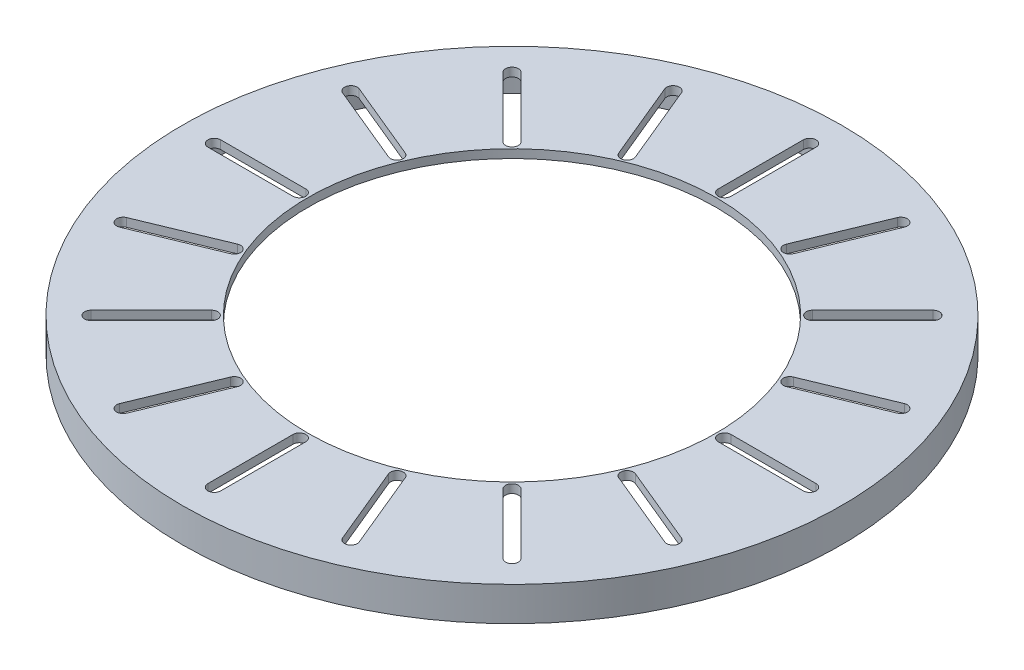
SolidWorks part; units mm, degrees
ref_plane "Front Plane" through (0, 0, 0) normal (0, 0, 1) x (1, 0, 0)
ref_plane "Top Plane" through (0, 0, 0) normal (0, 1, 0) x (1, 0, 0)
ref_plane "Right Plane" through (0, 0, 0) normal (1, 0, 0) x (0, 0, -1)
sketch "Sketch1" plane through (0, 0, 0) normal (0, 1, 0) x (1, 0, 0)
  circle A0 centre (0, 0) radius 37.6
  circle A1 centre (0, 0) radius 38.75
  dimension "D1" = 75.2
  dimension "D2" = 77.5
extrude "Boss-Extrude1" add sketch "Sketch1" along normal blind 3
sketch "Sketch2" plane through (0, 3, 0) normal (0, 1, 0) x (1, 0, 0)
  circle A0 centre (0, 0) radius 38.75
  circle A1 centre (0, 0) radius 24
  circle A2 centre (0, 0) radius 38.75 construction
  dimension "D1" = 48
extrude "Boss-Extrude2" add sketch "Sketch2" along normal blind 1
sketch "Sketch3" plane through (0, 4, 0) normal (0, 1, 0) x (1, 0, 0)
  line L0 (0, 0) -> (0, 31.25) construction
  line L1 (8, 31.25) -> (8, 34.6962) construction
  line L2 (0, 31.25) -> (8, 31.25) construction
  line L3 (8, 34.6962) -> (-8, 27.8038) construction
  line L4 (0, 31.25) -> (-8, 31.25) construction
  line L5 (-8, 31.25) -> (-8, 27.8038) construction
  line L6 (0, 31.25) -> (12.3634, 2.5497) construction
  line L7 (0, 0) -> (-8, 27.8038) construction
  arc A0 (-8, 27.8038) -> (8, 34.6962) centre (12.3634, 2.5497) cw construction
  arc A1 (7.8991, 35.4394) -> (-8.4708, 28.3876) centre (12.3634, 2.5497) ccw
  arc A2 (8.1009, 33.953) -> (-7.5292, 27.2199) centre (12.3634, 2.5497) ccw
  arc A3 (8.1009, 33.953) -> (7.8991, 35.4394) centre (8, 34.6962) ccw
  arc A4 (-8.4708, 28.3876) -> (-7.5292, 27.2199) centre (-8, 27.8038) ccw
  arc A5 (3.249, 28.7488) -> (20.6687, 28.9937) centre (12.398, -2.3757) cw construction
  arc A6 (20.8599, 29.7189) -> (3.0375, 29.4684) centre (12.398, -2.3757) ccw
  arc A7 (20.4775, 28.2684) -> (3.4605, 28.0293) centre (12.398, -2.3757) ccw
  arc A8 (20.4775, 28.2684) -> (20.8599, 29.7189) centre (20.6687, 28.9937) ccw
  arc A9 (3.0375, 29.4684) -> (3.4605, 28.0293) centre (3.249, 28.7488) ccw
  arc A10 (14.0034, 25.3171) -> (30.1908, 18.8771) centre (10.5452, -6.9394) cw construction
  arc A11 (30.645, 19.4739) -> (14.0833, 26.0628) centre (10.5452, -6.9394) ccw
  arc A12 (29.7366, 18.2802) -> (13.9234, 24.5714) centre (10.5452, -6.9394) ccw
  arc A13 (29.7366, 18.2802) -> (30.645, 19.4739) centre (30.1908, 18.8771) ccw
  arc A14 (14.0833, 26.0628) -> (13.9234, 24.5714) centre (14.0034, 25.3171) ccw
  arc A15 (22.6259, 18.0311) -> (35.1166, 5.8866) centre (7.0869, -10.4466) cw construction
  arc A16 (35.7646, 6.2642) -> (22.9851, 18.6895) centre (7.0869, -10.4466) ccw
  arc A17 (34.4686, 5.509) -> (22.2666, 17.3727) centre (7.0869, -10.4466) ccw
  arc A18 (34.4686, 5.509) -> (35.7646, 6.2642) centre (35.1166, 5.8866) ccw
  arc A19 (22.9851, 18.6895) -> (22.2666, 17.3727) centre (22.6259, 18.0311) ccw
  arc A20 (27.8038, 8) -> (34.6962, -8) centre (2.5497, -12.3634) cw construction
  arc A21 (35.4394, -7.8991) -> (28.3876, 8.4708) centre (2.5497, -12.3634) ccw
  arc A22 (33.953, -8.1009) -> (27.2199, 7.5292) centre (2.5497, -12.3634) ccw
  arc A23 (33.953, -8.1009) -> (35.4394, -7.8991) centre (34.6962, -8) ccw
  arc A24 (28.3876, 8.4708) -> (27.2199, 7.5292) centre (27.8038, 8) ccw
  arc A25 (28.7488, -3.249) -> (28.9937, -20.6687) centre (-2.3757, -12.398) cw construction
  arc A26 (29.7189, -20.8599) -> (29.4684, -3.0375) centre (-2.3757, -12.398) ccw
  arc A27 (28.2684, -20.4775) -> (28.0293, -3.4605) centre (-2.3757, -12.398) ccw
  arc A28 (28.2684, -20.4775) -> (29.7189, -20.8599) centre (28.9937, -20.6687) ccw
  arc A29 (29.4684, -3.0375) -> (28.0293, -3.4605) centre (28.7488, -3.249) ccw
  arc A30 (25.3171, -14.0034) -> (18.8771, -30.1908) centre (-6.9394, -10.5452) cw construction
  arc A31 (19.4739, -30.645) -> (26.0628, -14.0833) centre (-6.9394, -10.5452) ccw
  arc A32 (18.2802, -29.7366) -> (24.5714, -13.9234) centre (-6.9394, -10.5452) ccw
  arc A33 (18.2802, -29.7366) -> (19.4739, -30.645) centre (18.8771, -30.1908) ccw
  arc A34 (26.0628, -14.0833) -> (24.5714, -13.9234) centre (25.3171, -14.0034) ccw
  arc A35 (18.0311, -22.6259) -> (5.8866, -35.1166) centre (-10.4466, -7.0869) cw construction
  arc A36 (6.2642, -35.7646) -> (18.6895, -22.9851) centre (-10.4466, -7.0869) ccw
  arc A37 (5.509, -34.4686) -> (17.3727, -22.2666) centre (-10.4466, -7.0869) ccw
  arc A38 (5.509, -34.4686) -> (6.2642, -35.7646) centre (5.8866, -35.1166) ccw
  arc A39 (18.6895, -22.9851) -> (17.3727, -22.2666) centre (18.0311, -22.6259) ccw
  arc A40 (8, -27.8038) -> (-8, -34.6962) centre (-12.3634, -2.5497) cw construction
  arc A41 (-7.8991, -35.4394) -> (8.4708, -28.3876) centre (-12.3634, -2.5497) ccw
  arc A42 (-8.1009, -33.953) -> (7.5292, -27.2199) centre (-12.3634, -2.5497) ccw
  arc A43 (-8.1009, -33.953) -> (-7.8991, -35.4394) centre (-8, -34.6962) ccw
  arc A44 (8.4708, -28.3876) -> (7.5292, -27.2199) centre (8, -27.8038) ccw
  arc A45 (-3.249, -28.7488) -> (-20.6687, -28.9937) centre (-12.398, 2.3757) cw construction
  arc A46 (-20.8599, -29.7189) -> (-3.0375, -29.4684) centre (-12.398, 2.3757) ccw
  arc A47 (-20.4775, -28.2684) -> (-3.4605, -28.0293) centre (-12.398, 2.3757) ccw
  arc A48 (-20.4775, -28.2684) -> (-20.8599, -29.7189) centre (-20.6687, -28.9937) ccw
  arc A49 (-3.0375, -29.4684) -> (-3.4605, -28.0293) centre (-3.249, -28.7488) ccw
  arc A50 (-14.0034, -25.3171) -> (-30.1908, -18.8771) centre (-10.5452, 6.9394) cw construction
  arc A51 (-30.645, -19.4739) -> (-14.0833, -26.0628) centre (-10.5452, 6.9394) ccw
  arc A52 (-29.7366, -18.2802) -> (-13.9234, -24.5714) centre (-10.5452, 6.9394) ccw
  arc A53 (-29.7366, -18.2802) -> (-30.645, -19.4739) centre (-30.1908, -18.8771) ccw
  arc A54 (-14.0833, -26.0628) -> (-13.9234, -24.5714) centre (-14.0034, -25.3171) ccw
  arc A55 (-22.6259, -18.0311) -> (-35.1166, -5.8866) centre (-7.0869, 10.4466) cw construction
  arc A56 (-35.7646, -6.2642) -> (-22.9851, -18.6895) centre (-7.0869, 10.4466) ccw
  arc A57 (-34.4686, -5.509) -> (-22.2666, -17.3727) centre (-7.0869, 10.4466) ccw
  arc A58 (-34.4686, -5.509) -> (-35.7646, -6.2642) centre (-35.1166, -5.8866) ccw
  arc A59 (-22.9851, -18.6895) -> (-22.2666, -17.3727) centre (-22.6259, -18.0311) ccw
  arc A60 (-27.8038, -8) -> (-34.6962, 8) centre (-2.5497, 12.3634) cw construction
  arc A61 (-35.4394, 7.8991) -> (-28.3876, -8.4708) centre (-2.5497, 12.3634) ccw
  arc A62 (-33.953, 8.1009) -> (-27.2199, -7.5292) centre (-2.5497, 12.3634) ccw
  arc A63 (-33.953, 8.1009) -> (-35.4394, 7.8991) centre (-34.6962, 8) ccw
  arc A64 (-28.3876, -8.4708) -> (-27.2199, -7.5292) centre (-27.8038, -8) ccw
  arc A65 (-28.7488, 3.249) -> (-28.9937, 20.6687) centre (2.3757, 12.398) cw construction
  arc A66 (-29.7189, 20.8599) -> (-29.4684, 3.0375) centre (2.3757, 12.398) ccw
  arc A67 (-28.2684, 20.4775) -> (-28.0293, 3.4605) centre (2.3757, 12.398) ccw
  arc A68 (-28.2684, 20.4775) -> (-29.7189, 20.8599) centre (-28.9937, 20.6687) ccw
  arc A69 (-29.4684, 3.0375) -> (-28.0293, 3.4605) centre (-28.7488, 3.249) ccw
  arc A70 (-25.3171, 14.0034) -> (-18.8771, 30.1908) centre (6.9394, 10.5452) cw construction
  arc A71 (-19.4739, 30.645) -> (-26.0628, 14.0833) centre (6.9394, 10.5452) ccw
  arc A72 (-18.2802, 29.7366) -> (-24.5714, 13.9234) centre (6.9394, 10.5452) ccw
  arc A73 (-18.2802, 29.7366) -> (-19.4739, 30.645) centre (-18.8771, 30.1908) ccw
  arc A74 (-26.0628, 14.0833) -> (-24.5714, 13.9234) centre (-25.3171, 14.0034) ccw
  arc A75 (-18.0311, 22.6259) -> (-5.8866, 35.1166) centre (10.4466, 7.0869) cw construction
  arc A76 (-6.2642, 35.7646) -> (-18.6895, 22.9851) centre (10.4466, 7.0869) ccw
  arc A77 (-5.509, 34.4686) -> (-17.3727, 22.2666) centre (10.4466, 7.0869) ccw
  arc A78 (-5.509, 34.4686) -> (-6.2642, 35.7646) centre (-5.8866, 35.1166) ccw
  arc A79 (-18.6895, 22.9851) -> (-17.3727, 22.2666) centre (-18.0311, 22.6259) ccw
  circle A80 centre (0, 0) radius 38.75 construction
  point P9 (-0.4713, 32.3441)
  point P19 (11.9421, 30.0624)
  point P27 (22.5375, 23.204)
  point P35 (29.7017, 12.813)
  point P43 (32.3441, 0.4713)
  point P51 (30.0624, -11.9421)
  point P59 (23.204, -22.5375)
  point P67 (12.813, -29.7017)
  point P75 (0.4713, -32.3441)
  point P83 (-11.9421, -30.0624)
  point P91 (-22.5375, -23.204)
  point P99 (-29.7017, -12.813)
  point P107 (-32.3441, -0.4713)
  point P115 (-30.0624, 11.9421)
  point P123 (-23.204, 22.5375)
  point P131 (-12.813, 29.7017)
  dimension "D1" = 31.25
  dimension "D2" = 8
  dimension "D3" = 0.75
  dimension "D4" = 32.4413
  dimension "D5" = 28.9318
extrude "Cut-Extrude1" [suppressed] cut sketch "Sketch3" against normal through all
sketch "Sketch4" plane through (0, 4, 0) normal (0, 1, 0) x (1, 0, 0)
  line L5 (0, 25) -> (0, 35) construction
  line L6 (-0.75, 25) -> (-0.75, 35)
  line L10 (0.75, 25) -> (0.75, 35)
  line L11 (9.5671, 23.097) -> (13.3939, 32.3358) construction
  line L16 (8.8742, 23.384) -> (12.701, 32.6228)
  line L17 (10.26, 22.81) -> (14.0868, 32.0488)
  line L22 (17.6777, 17.6777) -> (24.7487, 24.7487) construction
  line L23 (17.1473, 18.208) -> (24.2184, 25.2791)
  line L28 (18.208, 17.1473) -> (25.2791, 24.2184)
  line L29 (23.097, 9.5671) -> (32.3358, 13.3939) construction
  line L34 (22.81, 10.26) -> (32.0488, 14.0868)
  line L35 (23.384, 8.8742) -> (32.6228, 12.701)
  line L40 (25, 0) -> (35, 0) construction
  line L41 (25, 0.75) -> (35, 0.75)
  line L46 (25, -0.75) -> (35, -0.75)
  line L47 (23.097, -9.5671) -> (32.3358, -13.3939) construction
  line L52 (23.384, -8.8742) -> (32.6228, -12.701)
  line L53 (22.81, -10.26) -> (32.0488, -14.0868)
  line L58 (17.6777, -17.6777) -> (24.7487, -24.7487) construction
  line L59 (18.208, -17.1473) -> (25.2791, -24.2184)
  line L64 (17.1473, -18.208) -> (24.2184, -25.2791)
  line L65 (9.5671, -23.097) -> (13.3939, -32.3358) construction
  line L70 (10.26, -22.81) -> (14.0868, -32.0488)
  line L71 (8.8742, -23.384) -> (12.701, -32.6228)
  line L76 (0, -25) -> (0, -35) construction
  line L77 (0.75, -25) -> (0.75, -35)
  line L82 (-0.75, -25) -> (-0.75, -35)
  line L83 (-9.5671, -23.097) -> (-13.3939, -32.3358) construction
  line L88 (-8.8742, -23.384) -> (-12.701, -32.6228)
  line L89 (-10.26, -22.81) -> (-14.0868, -32.0488)
  line L94 (-17.6777, -17.6777) -> (-24.7487, -24.7487) construction
  line L95 (-17.1473, -18.208) -> (-24.2184, -25.2791)
  line L96 (-18.208, -17.1473) -> (-25.2791, -24.2184)
  line L98 (-23.097, -9.5671) -> (-32.3358, -13.3939) construction
  line L99 (-22.81, -10.26) -> (-32.0488, -14.0868)
  line L100 (-23.384, -8.8742) -> (-32.6228, -12.701)
  line L101 (-25, 0) -> (-35, 0) construction
  line L102 (-25, -0.75) -> (-35, -0.75)
  line L103 (-25, 0.75) -> (-35, 0.75)
  line L104 (-23.097, 9.5671) -> (-32.3358, 13.3939) construction
  line L105 (-23.384, 8.8742) -> (-32.6228, 12.701)
  line L106 (-22.81, 10.26) -> (-32.0488, 14.0868)
  line L107 (-17.6777, 17.6777) -> (-24.7487, 24.7487) construction
  line L108 (-18.208, 17.1473) -> (-25.2791, 24.2184)
  line L109 (-17.1473, 18.208) -> (-24.2184, 25.2791)
  line L110 (-9.5671, 23.097) -> (-13.3939, 32.3358) construction
  line L111 (-10.26, 22.81) -> (-14.0868, 32.0488)
  line L112 (-8.8742, 23.384) -> (-12.701, 32.6228)
  line L113 (0, 0) -> (0, 25) construction
  arc A0 (-0.75, 25) -> (0.75, 25) centre (0, 25) ccw
  arc A1 (0.75, 35) -> (-0.75, 35) centre (0, 35) ccw
  circle A2 centre (0, 0) radius 24 construction
  arc A3 (8.8742, 23.384) -> (10.26, 22.81) centre (9.5671, 23.097) ccw
  arc A4 (14.0868, 32.0488) -> (12.701, 32.6228) centre (13.3939, 32.3358) ccw
  arc A5 (17.1473, 18.208) -> (18.208, 17.1473) centre (17.6777, 17.6777) ccw
  arc A6 (25.2791, 24.2184) -> (24.2184, 25.2791) centre (24.7487, 24.7487) ccw
  arc A7 (22.81, 10.26) -> (23.384, 8.8742) centre (23.097, 9.5671) ccw
  arc A8 (32.6228, 12.701) -> (32.0488, 14.0868) centre (32.3358, 13.3939) ccw
  arc A9 (25, 0.75) -> (25, -0.75) centre (25, 0) ccw
  arc A10 (35, -0.75) -> (35, 0.75) centre (35, 0) ccw
  arc A11 (23.384, -8.8742) -> (22.81, -10.26) centre (23.097, -9.5671) ccw
  arc A12 (32.0488, -14.0868) -> (32.6228, -12.701) centre (32.3358, -13.3939) ccw
  arc A13 (18.208, -17.1473) -> (17.1473, -18.208) centre (17.6777, -17.6777) ccw
  arc A14 (24.2184, -25.2791) -> (25.2791, -24.2184) centre (24.7487, -24.7487) ccw
  arc A15 (10.26, -22.81) -> (8.8742, -23.384) centre (9.5671, -23.097) ccw
  arc A16 (12.701, -32.6228) -> (14.0868, -32.0488) centre (13.3939, -32.3358) ccw
  arc A17 (0.75, -25) -> (-0.75, -25) centre (0, -25) ccw
  arc A18 (-0.75, -35) -> (0.75, -35) centre (0, -35) ccw
  arc A19 (-8.8742, -23.384) -> (-10.26, -22.81) centre (-9.5671, -23.097) ccw
  arc A20 (-14.0868, -32.0488) -> (-12.701, -32.6228) centre (-13.3939, -32.3358) ccw
  arc A21 (-17.1473, -18.208) -> (-18.208, -17.1473) centre (-17.6777, -17.6777) ccw
  arc A22 (-25.2791, -24.2184) -> (-24.2184, -25.2791) centre (-24.7487, -24.7487) ccw
  arc A23 (-22.81, -10.26) -> (-23.384, -8.8742) centre (-23.097, -9.5671) ccw
  arc A24 (-32.6228, -12.701) -> (-32.0488, -14.0868) centre (-32.3358, -13.3939) ccw
  arc A25 (-25, -0.75) -> (-25, 0.75) centre (-25, 0) ccw
  arc A26 (-35, 0.75) -> (-35, -0.75) centre (-35, 0) ccw
  arc A27 (-23.384, 8.8742) -> (-22.81, 10.26) centre (-23.097, 9.5671) ccw
  arc A28 (-32.0488, 14.0868) -> (-32.6228, 12.701) centre (-32.3358, 13.3939) ccw
  arc A29 (-18.208, 17.1473) -> (-17.1473, 18.208) centre (-17.6777, 17.6777) ccw
  arc A30 (-24.2184, 25.2791) -> (-25.2791, 24.2184) centre (-24.7487, 24.7487) ccw
  arc A31 (-10.26, 22.81) -> (-8.8742, 23.384) centre (-9.5671, 23.097) ccw
  arc A32 (-12.701, 32.6228) -> (-14.0868, 32.0488) centre (-13.3939, 32.3358) ccw
  point P2 (0, 30)
  point P9 (0, 0)
  point P13 (11.4805, 27.7164)
  point P20 (21.2132, 21.2132)
  point P27 (27.7164, 11.4805)
  point P34 (30, 0)
  point P41 (27.7164, -11.4805)
  point P48 (21.2132, -21.2132)
  point P55 (11.4805, -27.7164)
  point P62 (0, -30)
  point P69 (-11.4805, -27.7164)
  point P76 (-21.2132, -21.2132)
  point P83 (-27.7164, -11.4805)
  point P90 (-30, 0)
  point P97 (-27.7164, 11.4805)
  point P104 (-21.2132, 21.2132)
  point P111 (-11.4805, 27.7164)
  dimension "D3" = 0.75
  dimension "D1" = 10
  dimension "D2" = 30
extrude "Cut-Extrude3" cut sketch "Sketch4" against normal blind 1
